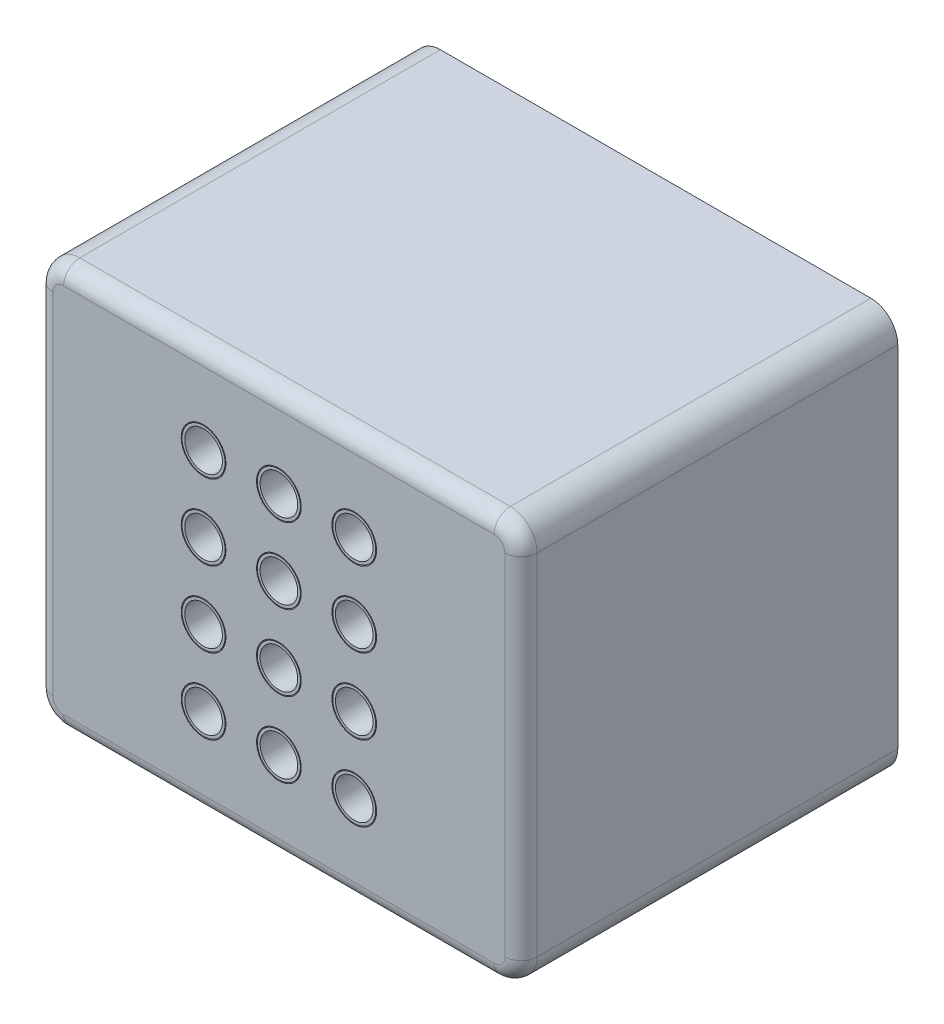
SolidWorks part; units mm, degrees
ref_plane "前视基准面" through (0, 0, 0) normal (0, 0, 1) x (1, 0, 0)
ref_plane "上视基准面" through (0, 0, 0) normal (0, 1, 0) x (1, 0, 0)
ref_plane "右视基准面" through (0, 0, 0) normal (1, 0, 0) x (0, 0, -1)
sketch "草图1" plane through (0, 0, 0) normal (0, 0, 1) x (1, 0, 0)
  line L1 (-45, 37.5) -> (45, 37.5)
  line L2 (-45, 37.5) -> (-45, -37.5)
  line L3 (-45, -37.5) -> (45, -37.5)
  line L4 (45, 37.5) -> (45, -37.5)
  line L5 (0, -37.5) -> (0, 37.5) construction
  line L6 (-45, 0) -> (45, 0) construction
  point P0 (0, 0)
  dimension "D1" = 75
  dimension "D2" = 90
extrude "凸台-拉伸1" add sketch "草图1" along normal blind 43
sketch "草图2" plane through (0, 0, 43) normal (0, 0, 1) x (1, 0, 0)
  line L0 (-45, 37.5) -> (45, -37.5) construction
  line L1 (0, 0) -> (0, 37.5) construction
  line L2 (45, 37.5) -> (-45, 37.5) construction
  line L3 (0, 0) -> (-45, 0) construction
  line L4 (-45, 37.5) -> (-45, -37.5) construction
  circle A0 centre (0, 7) radius 4.15
  circle A1 centre (0, -7) radius 4.15
  circle A2 centre (14, 7) radius 4.15
  circle A3 centre (14, -7) radius 4.15
  circle A4 centre (-14, -7) radius 4.15
  circle A5 centre (-14, 7) radius 4.15
  circle A6 centre (0, -21) radius 4.15
  circle A7 centre (-14, -21) radius 4.15
  circle A8 centre (14, -21) radius 4.15
  circle A9 centre (-14, 21) radius 4.15
  circle A10 centre (0, 21) radius 4.15
  circle A11 centre (14, 21) radius 4.15
  dimension "D1" = 8.3
  dimension "D6" = 8.3
  dimension "D8" = 8.3
  dimension "D9" = 8.3
  dimension "D2" = 14
  dimension "D4" = 14
  dimension "D5" = 14
  dimension "D7" = 14
  dimension "D3" = 2
extrude "切除-拉伸3" cut sketch "草图2" against normal blind 80
sketch "草图8" plane through (0, 0, 0) normal (0, 0, -1) x (-1, 0, 0)
  line L0 (-45, 37.5) -> (45, 37.5) construction
  line L1 (-42.5, 35) -> (42.5, 35)
  line L2 (-42.5, 35) -> (-42.5, -35)
  line L3 (-42.5, -35) -> (42.5, -35)
  line L4 (42.5, 35) -> (42.5, -35)
  line L5 (0, -35) -> (0, 35) construction
  line L6 (-42.5, 0) -> (42.5, 0) construction
  line L7 (45, 37.5) -> (45, -37.5) construction
  point P0 (0, 0)
  dimension "D1" = 2.5
  dimension "D2" = 2.5
extrude "切除-拉伸4" cut sketch "草图8" against normal blind 37
sketch "草图9" plane through (0, 0, 37) normal (0, 0, -1) x (-1, 0, 0)
  line L0 (0, 0) -> (42.5, 0) construction
  line L1 (42.5, -35) -> (42.5, 35) construction
  circle A0 centre (-14, 7) radius 4
  circle A1 centre (-14, 7) radius 6.5
  circle A2 centre (0, 7) radius 4
  circle A3 centre (0, 7) radius 6.5
  circle A4 centre (14, 7) radius 4
  circle A5 centre (14, 7) radius 6.5
  circle A6 centre (14, -7) radius 6.5
  circle A7 centre (14, -7) radius 4
  circle A8 centre (0, -7) radius 6.5
  circle A9 centre (0, -7) radius 4
  circle A10 centre (-14, -7) radius 6.5
  circle A11 centre (-14, -7) radius 4
  circle A12 centre (-14, 21) radius 4
  circle A13 centre (-14, 21) radius 6.5
  circle A14 centre (0, 21) radius 4
  circle A15 centre (0, 21) radius 6.5
  circle A16 centre (14, 21) radius 4
  circle A17 centre (14, 21) radius 6.5
  circle A18 centre (14, -21) radius 4
  circle A19 centre (0, -21) radius 4
  circle A20 centre (-14, -21) radius 4
  circle A21 centre (14, -21) radius 6.5
  circle A22 centre (0, -21) radius 6.5
  circle A23 centre (-14, -21) radius 6.5
  dimension "D1" = 13
  dimension "D2" = 3
  dimension "D3" = 13
  dimension "D4" = 13
  dimension "D5" = 13
extrude "凸台-拉伸5" add sketch "草图9" along normal blind 22
sketch "草图12" plane through (0, 0, 15) normal (0, 0, -1) x (-1, 0, 0)
  line L0 (-1.5, 18.5) -> (1.5, 18.5)
  line L1 (-1.5, 18.5) -> (-1.5, 8.5)
  line L2 (1.5, 18.5) -> (1.5, 8.5)
  line L3 (-1.5, 8.5) -> (1.5, 8.5)
  line L4 (12.5, 18.5) -> (15.5, 18.5)
  line L5 (12.5, 18.5) -> (12.5, 8.5)
  line L6 (15.5, 18.5) -> (15.5, 8.5)
  line L7 (-15.5, 18.5) -> (-12.5, 18.5)
  line L8 (-15.5, 18.5) -> (-15.5, 8.5)
  line L9 (-15.5, 8.5) -> (-12.5, 8.5)
  line L10 (-12.5, 18.5) -> (-12.5, 8.5)
  line L11 (-14, 8.5) -> (-14, 18.5) construction
  line L12 (-15.5, 13.5) -> (-12.5, 13.5) construction
  line L13 (12.5, 8.5) -> (15.5, 8.5)
  line L14 (-1.5, -7.5) -> (1.5, -7.5)
  line L15 (-1.5, -7.5) -> (-1.5, -17.5)
  line L16 (1.5, -7.5) -> (1.5, -17.5)
  line L17 (-1.5, -17.5) -> (1.5, -17.5)
  line L18 (12.5, -7.5) -> (15.5, -7.5)
  line L19 (12.5, -7.5) -> (12.5, -17.5)
  line L20 (15.5, -7.5) -> (15.5, -17.5)
  line L21 (-15.5, -7.5) -> (-12.5, -7.5)
  line L22 (-15.5, -7.5) -> (-15.5, -17.5)
  line L23 (-15.5, -17.5) -> (-12.5, -17.5)
  line L24 (-12.5, -7.5) -> (-12.5, -17.5)
  line L25 (12.5, -17.5) -> (15.5, -17.5)
  line L26 (-14, -17.5) -> (-14, -7.5) construction
  line L27 (-15.5, -12.5) -> (-12.5, -12.5) construction
  circle A2 centre (-14, 7) radius 6.5 construction
  circle A3 centre (-14, 7) radius 6.5 construction
  point P8 (-14, 13.5)
  point P23 (-14, -12.5)
  dimension "D1" = 3
  dimension "D2" = 2
  dimension "D3" = 10
  dimension "D4" = 3
extrude "切除-拉伸5" cut sketch "草图12" against normal blind 4
sketch "草图13" plane through (0, 0, 37) normal (0, 0, -1) x (-1, 0, 0)
  line L0 (0, 7) -> (14, 7) construction
  line L1 (0, 0) -> (0, 17.1437) construction
  line L2 (-14, 7) -> (0, -7) construction
  circle A0 centre (-7, 0) radius 1.25
  circle A2 centre (-7, 0) radius 4
  circle A3 centre (7, 0) radius 1.25
  circle A4 centre (19, 0) radius 4
  circle A5 centre (7, 0) radius 4
  circle A6 centre (19, 0) radius 1.25
  circle A7 centre (-19, 0) radius 1.25
  circle A8 centre (-19, 0) radius 4
  dimension "D1" = 2.5
  dimension "D3" = 2
  dimension "D2" = 8
  dimension "D4" = 8
extrude "凸台-拉伸7" add sketch "草图13" along normal blind 22
sketch "草图15" plane through (0, 0, 43) normal (0, 0, 1) x (1, 0, 0)
  line L0 (0, 0) -> (-32.1578, 0) construction
  circle A0 centre (-14, 7) radius 3.5
  circle A1 centre (0, 7) radius 3.5
  circle A2 centre (14, 7) radius 3.5
  circle A3 centre (14, -7) radius 3.5
  circle A4 centre (0, -7) radius 3.5
  circle A5 centre (-14, -7) radius 3.5
  circle A6 centre (-14, 7) radius 4
  circle A7 centre (0, 7) radius 4
  circle A8 centre (14, 7) radius 4
  circle A9 centre (14, -7) radius 4
  circle A10 centre (0, -7) radius 4
  circle A11 centre (-14, -7) radius 4
  circle A12 centre (-14, 21) radius 3.5
  circle A13 centre (-14, 21) radius 4
  circle A14 centre (0, 21) radius 4
  circle A15 centre (14, 21) radius 4
  circle A16 centre (0, 21) radius 3.5
  circle A17 centre (14, 21) radius 3.5
  circle A18 centre (14, -21) radius 4
  circle A19 centre (14, -21) radius 3.5
  circle A20 centre (0, -21) radius 4
  circle A21 centre (0, -21) radius 3.5
  circle A22 centre (-14, -21) radius 4
  circle A23 centre (-14, -21) radius 3.5
  dimension "D1" = 7
  dimension "D3" = 7
  dimension "D4" = 7
  dimension "D5" = 7
  dimension "D2" = 3
extrude "凸台-拉伸8" add sketch "草图15" against normal blind 5.8
fillet "圆角1" radius 5 8 edges at (45, 37.5, 21.5) (-42.5, -35, 18.5) (42.5, -35, 18.5) (45, -37.5, 21.5) (-45, -37.5, 21.5) (-42.5, 35, 18.5) (-45, 37.5, 21.5) (42.5, 35, 18.5)
sketch "草图16" plane through (0, 0, 0) normal (0, 0, -1) x (-1, 0, 0)
  line L0 (-41.0355, 33.5355) -> (-37.5, 30) construction
  line L1 (0, 0) -> (0, 35) construction
  line L2 (37.5, 35) -> (-37.5, 35) construction
  line L3 (0, 0) -> (42.5, 0) construction
  line L4 (42.5, -30) -> (42.5, 30) construction
  line L5 (41.0355, 33.5355) -> (37.5, 30) construction
  line L6 (41.0355, -33.5355) -> (37.5, -30) construction
  line L7 (-41.0355, -33.5355) -> (-37.5, -30) construction
  arc A0 (-37.5, 35) -> (-42.5, 30) centre (-37.5, 30) ccw construction
  circle A2 centre (-40.3284, 32.8284) radius 1.4
  circle A3 centre (-40.3284, 32.8284) radius 4.5355
  circle A4 centre (40.3284, 32.8284) radius 4.5355
  circle A5 centre (40.3284, 32.8284) radius 1.4
  circle A6 centre (40.3284, -32.8284) radius 1.4
  circle A7 centre (40.3284, -32.8284) radius 4.5355
  circle A8 centre (-40.3284, -32.8284) radius 4.5355
  circle A9 centre (-40.3284, -32.8284) radius 1.4
  dimension "D1" = 2.8
  dimension "D2" = 4
extrude "凸台-拉伸9" add sketch "草图16" against normal blind 37
sketch "草图17" plane through (0, 0, 0) normal (0, 0, -1) x (-1, 0, 0)
  circle A0 centre (-40.3284, 32.8284) radius 1.4
  circle A1 centre (40.3284, 32.8284) radius 1.4
  circle A2 centre (40.3284, -32.8284) radius 1.4
  circle A3 centre (-40.3284, -32.8284) radius 1.4
extrude "切除-拉伸7" cut sketch "草图17" against normal blind 27
fillet "圆角3" radius 3 8 edges at (43.5355, 36.0355, 43) (45, 0, 43) (43.5355, -36.0355, 43) (0, -37.5, 43) (-43.5355, -36.0355, 43) (-45, 0, 43) (-43.5355, 36.0355, 43) (0, 37.5, 43)
sketch "草图18" plane through (0, -37.5, 0) normal (0, -1, 0) x (1, 0, 0)
  line L0 (40, 20) -> (-40, 20) construction
  line L1 (40, 0) -> (40, 40) construction
  line L2 (-40, 40) -> (-40, 0) construction
  circle A0 centre (25, 20) radius 6.5
  dimension "D2" = 13
  dimension "D1" = 15
extrude "切除-拉伸8" cut sketch "草图18" against normal blind 10
sketch "草图19" plane through (0, 0, 0) normal (0, 0, -1) x (-1, 0, 0)
  line L0 (-36.3466, -35) -> (36.3466, -35) construction
  line L1 (-34.5, -22) -> (-15.5, -22)
  line L2 (-34.5, -22) -> (-34.5, -35)
  line L3 (-34.5, -35) -> (-15.5, -35)
  line L4 (-15.5, -22) -> (-15.5, -35)
  line L5 (-25, -35) -> (-25, -22) construction
  line L6 (-34.5, -28.5) -> (-15.5, -28.5) construction
  line L8 (-45, -32.5) -> (-45, 32.5) construction
  point P0 (-25, -28.5)
  dimension "D1" = 19
  dimension "D2" = 13
  dimension "D3" = 20
sketch "草图24" plane through (0, -37.5, 0) normal (0, -1, 0) x (1, 0, 0)
  line L0 (-40, 40) -> (-40, 0) construction
  line L1 (-31.75, 24.25) -> (-18.25, 24.25)
  line L2 (-31.75, 24.25) -> (-31.75, 15.75)
  line L3 (-31.75, 15.75) -> (-18.25, 15.75)
  line L4 (-18.25, 24.25) -> (-18.25, 15.75)
  line L5 (-25, 15.75) -> (-25, 24.25) construction
  line L6 (-31.75, 20) -> (-18.25, 20) construction
  circle A0 centre (25, 20) radius 6.5 construction
  point P0 (-25, 20)
  dimension "D1" = 13.5
  dimension "D2" = 8.5
  dimension "D3" = 15
  dimension "D4" = 0
extrude "切除-拉伸12" cut sketch "草图24" against normal blind 3
sketch "草图25" plane through (-45, 0, 0) normal (-1, 0, 0) x (0, 0, 1)
  line L0 (0, 32.5) -> (0, -32.5) construction
  line L1 (0, -32.5) -> (40, -32.5) construction
  circle A0 centre (20, -22.5) radius 6
  dimension "D1" = 12
  dimension "D3" = 10
  dimension "D2" = 20
sketch "草图26" plane through (0, 0, 15) normal (0, 0, -1) x (-1, 0, 0)
  line L1 (-12.5, 14.6754) -> (-12.5, 17.2919) construction
  line L2 (-15.5, 18.5) -> (-12.5, 18.5)
  line L3 (-15.5, 18.5) -> (-15.5, 15.5)
  line L4 (-15.5, 15.5) -> (-12.5, 15.5)
  line L5 (-12.5, 18.5) -> (-12.5, 15.5)
  line L6 (-15.5, 18.5) -> (-12.5, 15.5) construction
  line L7 (-15.5, 15.5) -> (-12.5, 18.5) construction
  line L8 (1.5, 14.6754) -> (1.5, 17.2919) construction
  line L9 (-1.5, 18.5) -> (1.5, 18.5)
  line L10 (-1.5, 18.5) -> (-1.5, 15.5)
  line L11 (-1.5, 15.5) -> (1.5, 15.5)
  line L12 (1.5, 18.5) -> (1.5, 15.5)
  line L13 (-1.5, 18.5) -> (1.5, 15.5) construction
  line L14 (-1.5, 15.5) -> (1.5, 18.5) construction
  line L15 (15.5, 14.6754) -> (15.5, 17.2919) construction
  line L16 (12.5, 18.5) -> (15.5, 18.5)
  line L17 (12.5, 18.5) -> (12.5, 15.5)
  line L18 (12.5, 15.5) -> (15.5, 15.5)
  line L19 (15.5, 18.5) -> (15.5, 15.5)
  line L20 (12.5, 18.5) -> (15.5, 15.5) construction
  line L21 (12.5, 15.5) -> (15.5, 18.5) construction
  line L22 (0, 0) -> (14.764, 0) construction
  line L23 (-15.5, 12.5) -> (-12.5, 12.5)
  line L24 (-15.5, 12.5) -> (-15.5, 9.5)
  line L25 (-15.5, 9.5) -> (-12.5, 9.5)
  line L26 (-12.5, 12.5) -> (-12.5, 9.5)
  line L27 (-15.5, 12.5) -> (-12.5, 9.5) construction
  line L28 (-15.5, 9.5) -> (-12.5, 12.5) construction
  line L29 (-1.5, 12.5) -> (1.5, 12.5)
  line L30 (-1.5, 12.5) -> (-1.5, 9.5)
  line L31 (-1.5, 9.5) -> (1.5, 9.5)
  line L32 (1.5, 12.5) -> (1.5, 9.5)
  line L33 (-1.5, 12.5) -> (1.5, 9.5) construction
  line L34 (-1.5, 9.5) -> (1.5, 12.5) construction
  line L35 (12.5, 12.5) -> (15.5, 12.5)
  line L36 (12.5, 12.5) -> (12.5, 9.5)
  line L37 (12.5, 9.5) -> (15.5, 9.5)
  line L38 (15.5, 12.5) -> (15.5, 9.5)
  line L39 (12.5, 12.5) -> (15.5, 9.5) construction
  line L40 (12.5, 9.5) -> (15.5, 12.5) construction
  line L41 (12.5, -9.5) -> (15.5, -12.5) construction
  line L42 (12.5, -12.5) -> (15.5, -9.5) construction
  line L43 (-1.5, -9.5) -> (1.5, -12.5) construction
  line L44 (-1.5, -12.5) -> (1.5, -9.5) construction
  line L45 (-15.5, -9.5) -> (-12.5, -12.5) construction
  line L46 (-15.5, -12.5) -> (-12.5, -9.5) construction
  line L47 (12.5, -15.5) -> (15.5, -18.5) construction
  line L48 (12.5, -18.5) -> (15.5, -15.5) construction
  line L49 (-1.5, -15.5) -> (1.5, -18.5) construction
  line L50 (-1.5, -18.5) -> (1.5, -15.5) construction
  line L51 (-15.5, -15.5) -> (-12.5, -18.5) construction
  line L52 (-15.5, -18.5) -> (-12.5, -15.5) construction
  line L53 (15.5, -12.5) -> (15.5, -9.5)
  line L54 (12.5, -9.5) -> (15.5, -9.5)
  line L55 (12.5, -12.5) -> (12.5, -9.5)
  line L56 (12.5, -12.5) -> (15.5, -12.5)
  line L58 (1.5, -12.5) -> (1.5, -9.5)
  line L59 (-1.5, -9.5) -> (1.5, -9.5)
  line L60 (-1.5, -12.5) -> (-1.5, -9.5)
  line L61 (-1.5, -12.5) -> (1.5, -12.5)
  line L62 (-12.5, -12.5) -> (-12.5, -9.5)
  line L63 (-15.5, -9.5) -> (-12.5, -9.5)
  line L64 (-15.5, -12.5) -> (-15.5, -9.5)
  line L65 (-15.5, -12.5) -> (-12.5, -12.5)
  line L66 (15.5, -18.5) -> (15.5, -15.5)
  line L67 (12.5, -15.5) -> (15.5, -15.5)
  line L68 (12.5, -18.5) -> (12.5, -15.5)
  line L69 (12.5, -18.5) -> (15.5, -18.5)
  line L70 (1.5, -18.5) -> (1.5, -15.5)
  line L71 (-1.5, -15.5) -> (1.5, -15.5)
  line L72 (-1.5, -18.5) -> (-1.5, -15.5)
  line L73 (-1.5, -18.5) -> (1.5, -18.5)
  line L74 (-12.5, -18.5) -> (-12.5, -15.5)
  line L75 (-15.5, -15.5) -> (-12.5, -15.5)
  line L76 (-15.5, -18.5) -> (-15.5, -15.5)
  line L77 (-15.5, -18.5) -> (-12.5, -18.5)
  arc A4 (-15.5, 17.2919) -> (-12.5, 17.2919) centre (-14, 21) ccw construction
  arc A6 (-1.5, 17.2919) -> (1.5, 17.2919) centre (0, 21) ccw construction
  arc A9 (12.5, 17.2919) -> (15.5, 17.2919) centre (14, 21) ccw construction
  arc A10 (-12.5, 10.7081) -> (-15.5, 10.7081) centre (-14, 7) ccw construction
  arc A11 (1.5, 10.7081) -> (-1.5, 10.7081) centre (0, 7) ccw construction
  arc A12 (15.5, 10.7081) -> (12.5, 10.7081) centre (14, 7) ccw construction
  point P0 (-14, 17)
  point P10 (0, 17)
  point P20 (14, 17)
  point P30 (-14, 11)
  point P38 (0, 11)
  point P46 (14, 11)
  point P80 (14, -11)
  point P81 (0, -11)
  point P82 (-14, -11)
  point P83 (14, -17)
  point P84 (0, -17)
  point P85 (-14, -17)
  dimension "D1" = 3
  dimension "D3" = 3
  dimension "D4" = 3
  dimension "D5" = 3
  dimension "D6" = 3
  dimension "D2" = 3
extrude "切除-拉伸14" cut sketch "草图26" against normal blind 21
sketch "草图27" plane through (0, 0, 0) normal (0, 0, -1) x (-1, 0, 0)
  line L0 (36.3466, 35) -> (-36.3466, 35) construction
  line L1 (36.3466, 35) -> (-36.3466, 35)
  line L2 (42.5, -28.8466) -> (42.5, 28.8466) construction
  line L3 (42.5, -28.8466) -> (42.5, 28.8466)
  line L4 (-40, -37.5) -> (40, -37.5)
  line L5 (45, -32.5) -> (45, 32.5)
  line L6 (40, 37.5) -> (-40, 37.5)
  line L7 (-45, 32.5) -> (-45, -32.5)
  line L8 (-40, -37.5) -> (40, -37.5)
  line L9 (45, -32.5) -> (45, 32.5)
  line L10 (40, 37.5) -> (-40, 37.5)
  line L11 (-45, 32.5) -> (-45, -32.5)
  line L12 (-42.5, 28.8466) -> (-42.5, -28.8466) construction
  line L13 (-42.5, 28.8466) -> (-42.5, -28.8466)
  line L14 (-36.3466, -35) -> (36.3466, -35) construction
  line L15 (-36.3466, -35) -> (36.3466, -35)
  circle A0 centre (-40.3284, 32.8284) radius 1.4 construction
  circle A1 centre (-40.3284, 32.8284) radius 1.4
  arc A2 (-42.5, 28.8466) -> (-36.3466, 35) centre (-40.3284, 32.8284) ccw construction
  arc A3 (-42.5, 28.8466) -> (-36.3466, 35) centre (-40.3284, 32.8284) ccw
  arc A4 (-45, -32.5) -> (-40, -37.5) centre (-40, -32.5) ccw
  arc A5 (40, -37.5) -> (45, -32.5) centre (40, -32.5) ccw
  arc A6 (45, 32.5) -> (40, 37.5) centre (40, 32.5) ccw
  arc A7 (-40, 37.5) -> (-45, 32.5) centre (-40, 32.5) ccw
  arc A8 (-45, -32.5) -> (-40, -37.5) centre (-40, -32.5) ccw
  arc A9 (40, -37.5) -> (45, -32.5) centre (40, -32.5) ccw
  arc A10 (45, 32.5) -> (40, 37.5) centre (40, 32.5) ccw
  arc A11 (-40, 37.5) -> (-45, 32.5) centre (-40, 32.5) ccw
  arc A12 (36.3466, 35) -> (42.5, 28.8466) centre (40.3284, 32.8284) ccw construction
  arc A13 (36.3466, 35) -> (42.5, 28.8466) centre (40.3284, 32.8284) ccw
  arc A14 (-36.3466, -35) -> (-42.5, -28.8466) centre (-40.3284, -32.8284) ccw construction
  arc A15 (-36.3466, -35) -> (-42.5, -28.8466) centre (-40.3284, -32.8284) ccw
  arc A16 (42.5, -28.8466) -> (36.3466, -35) centre (40.3284, -32.8284) ccw construction
  arc A17 (42.5, -28.8466) -> (36.3466, -35) centre (40.3284, -32.8284) ccw
  circle A18 centre (40.3284, 32.8284) radius 1.4 construction
  circle A19 centre (40.3284, 32.8284) radius 1.4
  circle A20 centre (-40.3284, -32.8284) radius 1.4 construction
  circle A21 centre (-40.3284, -32.8284) radius 1.4
  circle A22 centre (40.3284, -32.8284) radius 1.4 construction
  circle A23 centre (40.3284, -32.8284) radius 1.4
  dimension "D1" = 0
extrude "凸台-拉伸10" add sketch "草图27" along normal blind 27
sketch "草图28" plane through (0, -37.5, 0) normal (0, -1, 0) x (1, 0, 0)
  circle A0 centre (25, 20) radius 6.5
